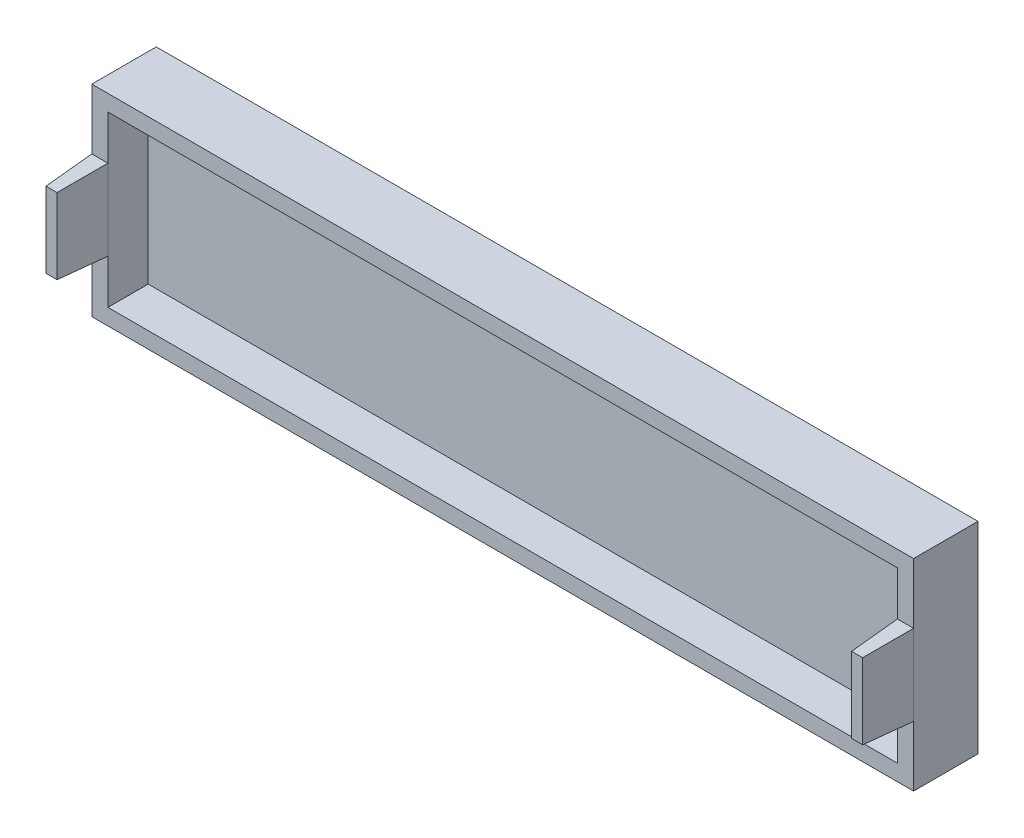
SolidWorks part; units mm, degrees
ref_plane "Piano frontale" through (0, 0, 0) normal (0, 0, 1) x (1, 0, 0)
ref_plane "Piano superiore" through (0, 0, 0) normal (0, 1, 0) x (1, 0, 0)
ref_plane "Piano destro" through (0, 0, 0) normal (1, 0, 0) x (0, 0, -1)
sketch "Schizzo1" plane through (0, 0, 0) normal (0, 0, 1) x (1, 0, 0)
  line L1 (51, -12.5) -> (-51, -12.5)
  line L2 (51, -12.5) -> (51, 12.5)
  line L3 (51, 12.5) -> (-51, 12.5)
  line L4 (-51, -12.5) -> (-51, 12.5)
  line L5 (51, -12.5) -> (-51, 12.5) construction
  line L6 (51, 12.5) -> (-51, -12.5) construction
  point P0 (0, 0)
  dimension "D1" = 102
  dimension "D2" = 25
extrude "Estrusione-Estrusione1" add sketch "Schizzo1" along normal blind 3
sketch "Schizzo2" plane through (0, 0, 3) normal (0, 0, 1) x (1, 0, 0)
  line L0 (49, 10.5) -> (-49, 10.5)
  line L1 (-49, 10.5) -> (-49, -10.5)
  line L2 (-49, -10.5) -> (49, -10.5)
  line L3 (49, -10.5) -> (49, 10.5)
  line L4 (-51, 12.5) -> (-51, -12.5)
  line L5 (-51, -12.5) -> (51, -12.5)
  line L6 (51, -12.5) -> (51, 12.5)
  line L7 (51, 12.5) -> (-51, 12.5)
  line L8 (-51, 12.5) -> (-51, -12.5)
  line L9 (-51, -12.5) -> (51, -12.5)
  line L10 (51, -12.5) -> (51, 12.5)
  line L11 (51, 12.5) -> (-51, 12.5)
  dimension "D1" = 0
  dimension "D2" = 2
extrude "Estrusione-Estrusione2" add sketch "Schizzo2" along normal blind 5
sketch "Schizzo3" plane through (0, 0, 8) normal (0, 0, 1) x (1, 0, 0)
  line L0 (-51, -5) -> (-51, 5)
  line L3 (-51, 12.5) -> (-51, -12.5) construction
  line L4 (-51, 5) -> (-49, 5)
  line L5 (-49, 10.5) -> (-49, -10.5) construction
  line L6 (-49, 5) -> (-49, -5)
  line L7 (-49, -5) -> (-51, -5)
  point P3 (-51, 0)
  dimension "D1" = 10
extrude "Estrusione-Estrusione3" add sketch "Schizzo3" along normal blind 6 draft 3
mirror "Specchia1" about plane through (0, 0, 0) normal (1, 0, 0) of "Estrusione-Estrusione3"
